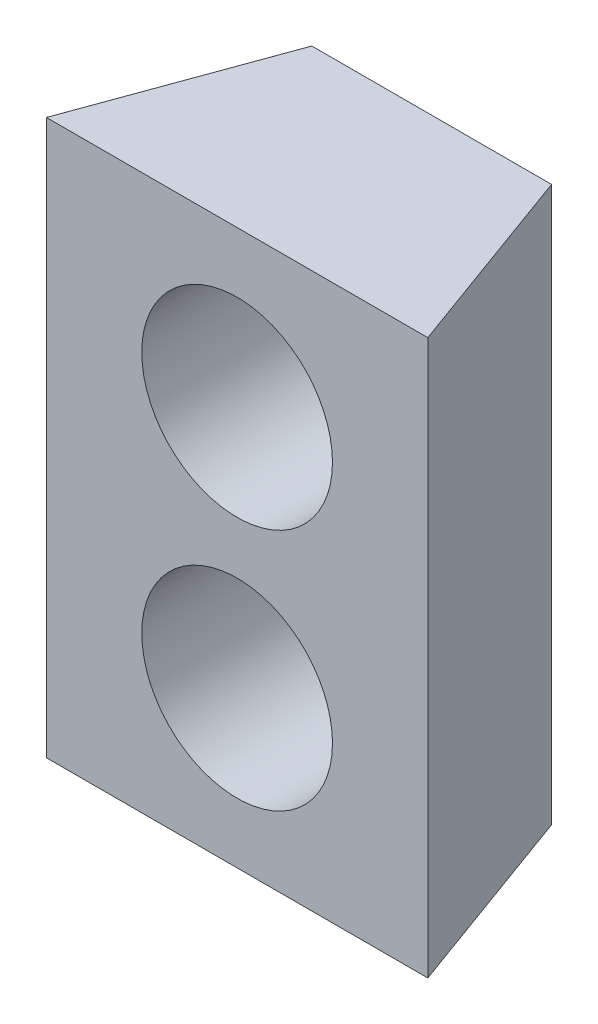
SolidWorks part; units mm, degrees
ref_plane "Front Plane" through (0, 0, 0) normal (0, 0, 1) x (1, 0, 0)
ref_plane "Top Plane" through (0, 0, 0) normal (0, 1, 0) x (1, 0, 0)
ref_plane "Right Plane" through (0, 0, 0) normal (1, 0, 0) x (0, 0, -1)
sketch "sketch1" plane through (0, 0, 0) normal (0, 0, 1) x (1, 0, 0)
  line L0 (6.223, 18.0975) -> (6.223, 0) construction
  line L1 (0, 0) -> (12.446, 0)
  line L2 (0, 0) -> (0, 18.0975)
  line L3 (0, 18.0975) -> (12.446, 18.0975)
  line L4 (12.446, 0) -> (12.446, 18.0975)
  circle A0 centre (6.223, 5.08) radius 3.1115
  circle A1 centre (6.223, 13.0175) radius 3.1115
  dimension "D3" = 6.223
  dimension "D5" = 6.223
  dimension "D4" = 7.9375
  dimension "D2" = 5.08
  dimension "D6" = 5.08
  dimension "D7" = 18.0975
  dimension "D1" = 12.446
extrude "Boss-Extrude1" add sketch "sketch1" along normal blind 6.35
sketch "Sketch2" plane through (0, 18.0975, 0) normal (0, 1, 0) x (1, 0, 0)
  line L0 (0, -6.35) -> (0, 0) construction
  line L1 (12.446, 0) -> (0, 0) construction
  line L2 (12.446, -6.35) -> (12.446, 0) construction
  line L3 (12.446, -6.35) -> (0, -6.35) construction
  line L4 (0, -6.35) -> (0, 0)
  line L5 (12.446, 0) -> (0, 0) construction
  line L6 (12.446, -6.35) -> (12.446, 0)
  line L7 (12.446, -6.35) -> (0, -6.35) construction
  line L8 (12.446, 0) -> (10.1348, 0)
  line L9 (10.1348, 0) -> (12.446, -6.35)
  line L10 (0, 0) -> (2.3112, 0)
  line L11 (2.3112, 0) -> (0, -6.35)
  line L12 (12.446, -6.35) -> (12.446, 0) construction
  line L13 (0, -6.35) -> (0, 0) construction
  point P11 (11.2904, 0)
  dimension "D1" = 20
  dimension "D2" = 20
extrude "Cut-Extrude1" cut sketch "Sketch2" against normal through all
sketch "Sketch3" plane through (0, 0, 0) normal (0, 0, -1) x (-1, 0, 0)
  circle A0 centre (-6.223, 5.08) radius 3.1115 construction
  circle A1 centre (-6.223, 13.0175) radius 3.1115 construction
  circle A2 centre (-6.223, 5.08) radius 3.1115
  circle A3 centre (-6.223, 13.0175) radius 3.1115
  circle A4 centre (-6.223, 13.0175) radius 2.8575
  circle A5 centre (-6.223, 5.08) radius 2.8575
  dimension "D1" = 0.254
extrude "Boss-Extrude2" add sketch "Sketch3" against normal offset from surface (1.27 mm away) 5.08 up to face at (6.223, 9.0488, 6.35)
equation "\"D5@sketch1\" = \"D3@sketch1\""
equation "\"D6@sketch1\"=.2"
equation "\"D2@Sketch2\"=\"D1@Sketch2\""
